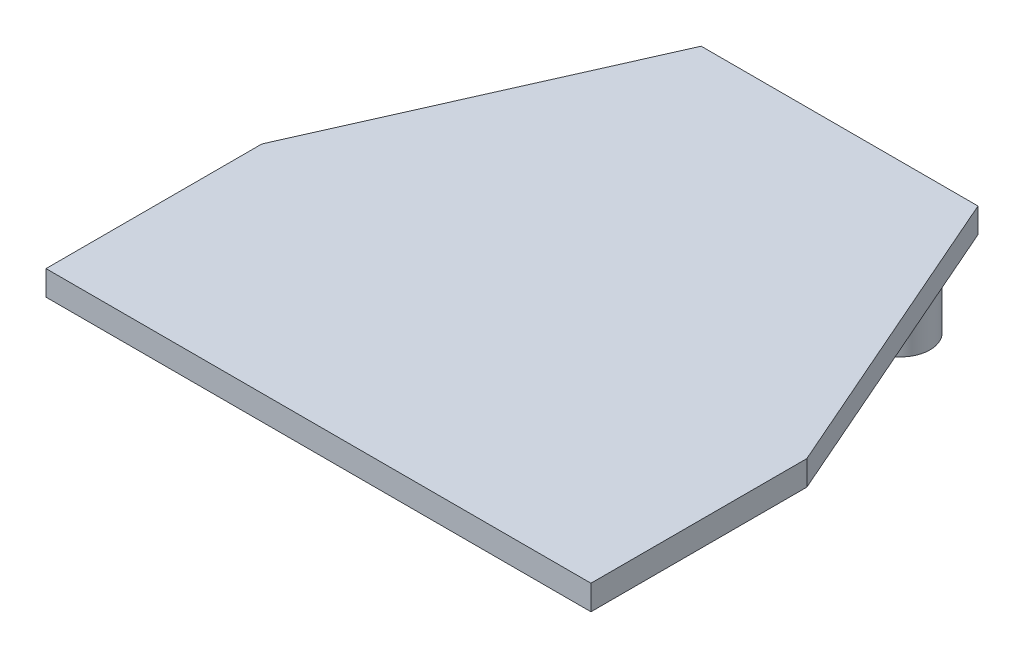
SolidWorks part; units mm, degrees
ref_plane "Front Plane" through (0, 0, 0) normal (0, 0, 1) x (1, 0, 0)
ref_plane "Top Plane" through (0, 0, 0) normal (0, 1, 0) x (1, 0, 0)
ref_plane "Right Plane" through (0, 0, 0) normal (1, 0, 0) x (0, 0, -1)
sketch "Sketch1" plane through (0, 0, 0) normal (0, 1, 0) x (1, 0, 0)
  line L6 (-22, 8.7143) -> (-22, -8.7143)
  line L7 (-22, -8.7143) -> (22, -8.7143)
  line L8 (22, 8.7143) -> (22, -8.7143)
  line L9 (-22, -8.7143) -> (22, -8.7143) construction
  line L10 (22, -8.7143) -> (22, 8.7143) construction
  line L11 (-22, 8.7143) -> (-11.1, 33.2857)
  line L12 (-11.1, 33.2857) -> (11.25, 33.2857)
  line L13 (11.25, 33.2857) -> (22, 8.7143)
  point P4 (0, -8.7143)
  point P5 (22, 0)
extrude "Boss-Extrude1" add sketch "Sketch1" along normal blind 2
sketch "Sketch3" plane through (0, 0, 0) normal (0, -1, 0) x (1, 0, 0)
  line L0 (-10, -3.2857) -> (10, -3.2857) construction
  line L1 (-9.9916, -28.2645) -> (10, -28.2857) construction
  circle A0 centre (-10, -3.2857) radius 2.375
  circle A1 centre (-9.9916, -28.2645) radius 2.3728
  circle A2 centre (10, -28.2857) radius 2.375
  circle A3 centre (10, -3.2857) radius 2.375
  point P11 (0, 0)
  dimension "D1" = 4.7457
  dimension "D2" = 4.75
  dimension "D3" = 4.75
  dimension "D4" = 4.75
extrude "Boss-Extrude3" add sketch "Sketch3" along normal blind 5
